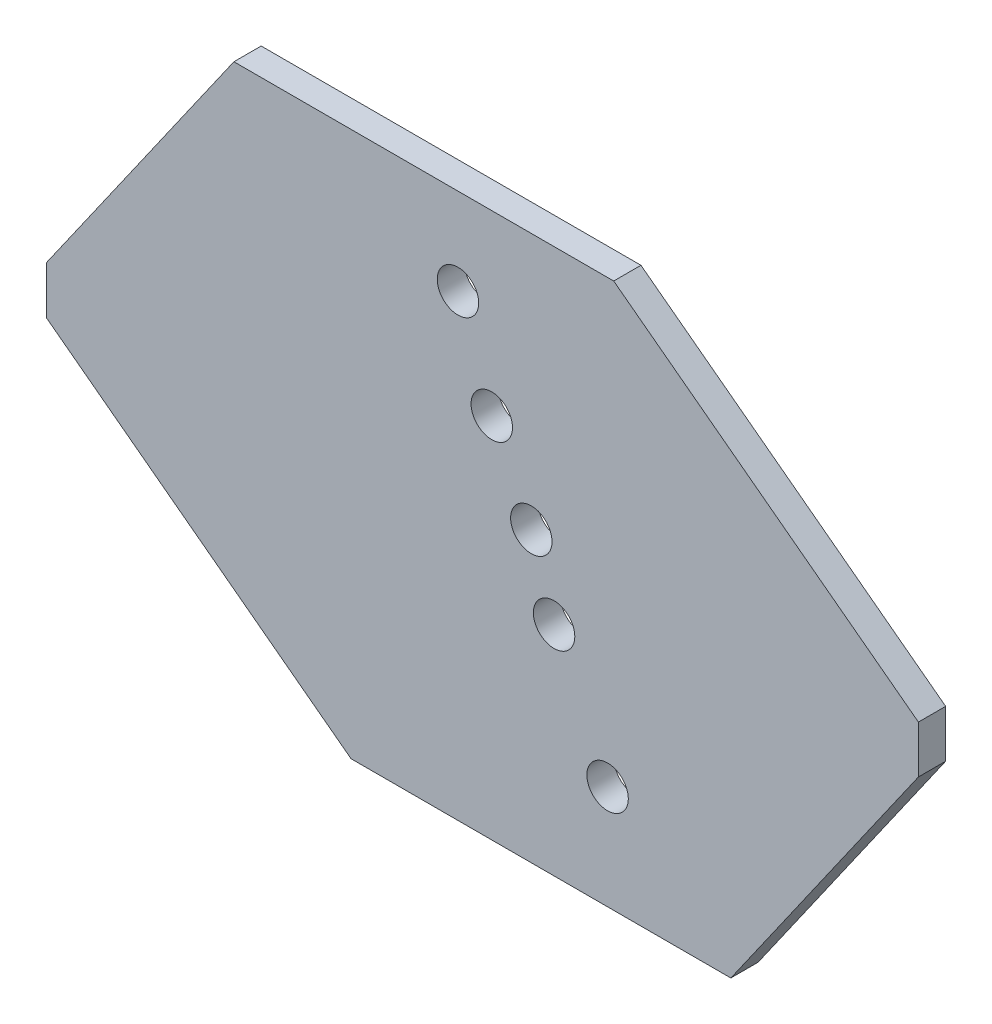
SolidWorks part; units mm, degrees
ref_plane "Front Plane" through (0, 0, 0) normal (0, 0, 1) x (1, 0, 0)
ref_plane "Top Plane" through (0, 0, 0) normal (0, 1, 0) x (1, 0, 0)
ref_plane "Right Plane" through (0, 0, 0) normal (1, 0, 0) x (0, 0, -1)
sketch "Sketch1" plane through (0, 0, 0) normal (0, 0, 1) x (1, 0, 0)
  line L1 (0, 0) -> (101.6, 0)
  line L2 (0, 0) -> (0, 63.5)
  line L3 (0, 63.5) -> (101.6, 63.5)
  line L4 (101.6, 0) -> (101.6, 63.5)
  dimension "D1" = 101.6
  dimension "D2" = 63.5
extrude "Boss-Extrude1" add sketch "Sketch1" along normal blind 3.175
sketch "Sketch2" plane through (0, 0, 3.175) normal (0, 0, 1) x (1, 0, 0)
  line L0 (101.6, 31.2097) -> (79.7467, 0)
  line L1 (101.6, 0) -> (101.6, 63.5) construction
  line L2 (0, 0) -> (101.6, 0) construction
  line L3 (101.6, 36.7493) -> (66.1007, 63.5)
  line L4 (101.6, 63.5) -> (0, 63.5) construction
  line L5 (66.1007, 63.5) -> (101.6, 63.5)
  line L6 (101.6, 63.5) -> (101.6, 36.7493)
  line L7 (101.6, 31.2097) -> (101.6, 0)
  line L8 (101.6, 0) -> (79.7467, 0)
  point P10 (77.0665, 23.6645)
  point P15 (77.0665, 26.5913)
  point P16 (52.6679, 56.6431)
  point P17 (57.6252, 63.5)
  point P18 (101.6, 27.0182)
  dimension "D1" = 55
  dimension "D2" = 37
  dimension "D3" = 38.1
  dimension "D4" = 44.45
extrude "Cut-Extrude1" cut sketch "Sketch2" against normal through all
sketch "Sketch3" plane through (0, 0, 3.175) normal (0, 0, 1) x (1, 0, 0)
  line L0 (21.8533, 63.5) -> (0, 32.2903)
  line L1 (66.1007, 63.5) -> (0, 63.5) construction
  line L2 (0, 63.5) -> (0, 0) construction
  line L3 (0, 32.2903) -> (0, 63.5)
  line L4 (0, 63.5) -> (21.8533, 63.5)
  line L5 (0, 0) -> (0, 26.7507)
  line L6 (0, 26.7507) -> (35.4993, 0)
  line L7 (0, 0) -> (79.7467, 0) construction
  line L8 (35.4993, 0) -> (0, 0)
  dimension "D1" = 55
  dimension "D2" = 38.1
  dimension "D3" = 44.45
  dimension "D4" = 37
extrude "Cut-Extrude2" cut sketch "Sketch3" against normal through all
sketch "Sketch5" plane through (0, 0, 3.175) normal (0, 0, 1) x (1, 0, 0)
  circle A0 centre (47.9581, 53.404) radius 2.413
  circle A1 centre (51.8946, 42.8028) radius 2.413
  circle A2 centre (59.1549, 25.3604) radius 2.413
  circle A3 centre (65.3895, 12.1029) radius 2.413
  circle A4 centre (56.5031, 33.6007) radius 2.413
  dimension "D1" = 4.826
  dimension "D2" = 4.826
  dimension "D3" = 4.826
  dimension "D4" = 4.826
  dimension "D5" = 4.826
extrude "Cut-Extrude3" cut sketch "Sketch5" against normal through all
